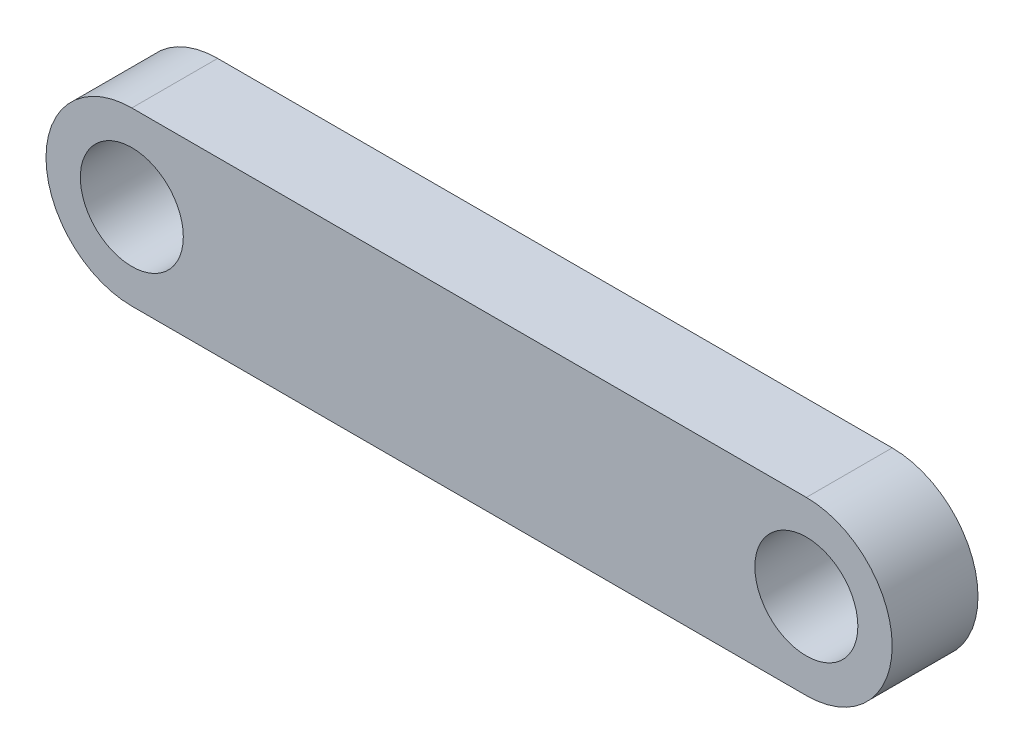
SolidWorks part; units mm, degrees
ref_plane "Front Plane" through (0, 0, 0) normal (0, 0, 1) x (1, 0, 0)
ref_plane "Top Plane" through (0, 0, 0) normal (0, 1, 0) x (1, 0, 0)
ref_plane "Right Plane" through (0, 0, 0) normal (1, 0, 0) x (0, 0, -1)
sketch "Sketch1" plane through (0, 0, 0) normal (0, 0, 1) x (1, 0, 0)
  line L0 (19.65, 0) -> (-19.65, 0) construction
  line L1 (19.65, -5) -> (-19.65, -5)
  line L2 (19.65, 5) -> (-19.65, 5)
  arc A0 (19.65, -5) -> (19.65, 5) centre (19.65, 0) ccw
  arc A1 (-19.65, 5) -> (-19.65, -5) centre (-19.65, 0) ccw
  circle A2 centre (-19.65, 0) radius 3
  point P2 (0, 0)
  dimension "D2" = 5
  dimension "D3" = 6
  dimension "D1" = 39.3
extrude "Boss-Extrude1" add sketch "Sketch1" along normal blind 5
sketch "Sketch2" plane through (0, 0, 0) normal (0, 0, -1) x (-1, 0, 0)
  circle A0 centre (-19.65, 0) radius 3
  dimension "D1" = 6
extrude "Cut-Extrude2" cut sketch "Sketch2" against normal blind 15 contours A0
